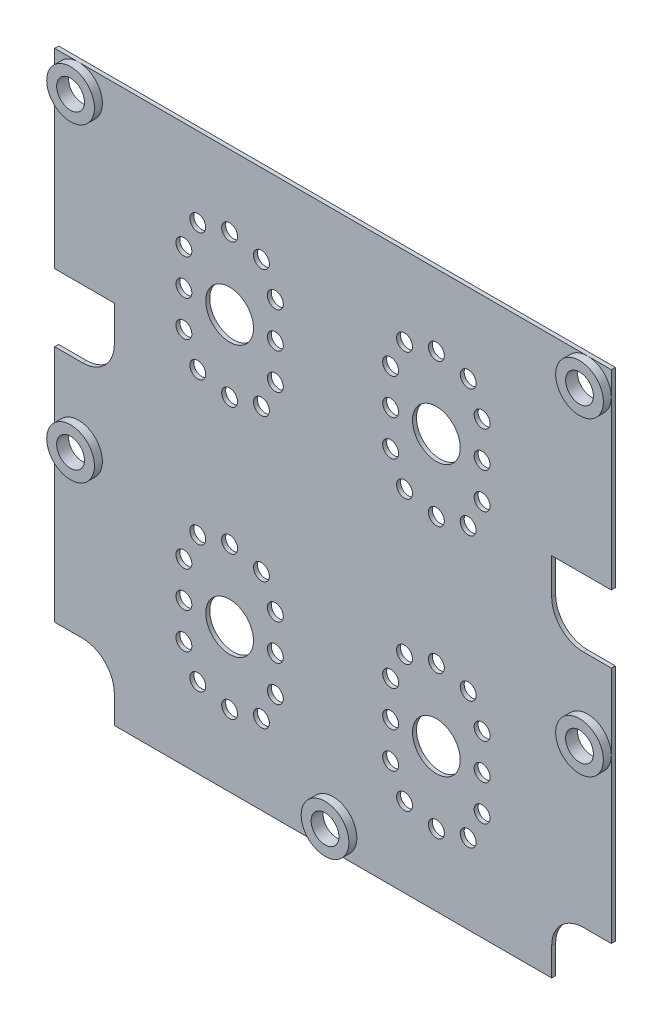
SolidWorks part; units mm, degrees
ref_plane "Front Plane" through (0, 0, 0) normal (0, 0, 1) x (1, 0, 0)
ref_plane "Top Plane" through (0, 0, 0) normal (0, 1, 0) x (1, 0, 0)
ref_plane "Right Plane" through (0, 0, 0) normal (1, 0, 0) x (0, 0, -1)
sketch "Sketch1" plane through (0, 0, 0) normal (0, 0, 1) x (1, 0, 0)
  line L1 (-35, -35) -> (35, -35)
  line L2 (-35, -35) -> (-35, 35)
  line L3 (-35, 35) -> (35, 35)
  line L4 (35, -35) -> (35, 35)
  line L5 (-35, -35) -> (35, 35) construction
  line L6 (-35, 35) -> (35, -35) construction
  point P0 (0, 0)
  dimension "D1" = 70
  dimension "D2" = 70
extrude "Boss-Extrude1" add sketch "Sketch1" along normal blind 0.5
sketch "Sketch2" plane through (0, 0, 0.5) normal (0, 0, 1) x (1, 0, 0)
  circle A0 centre (-13, 17) radius 3
  point P0 (-13, 17)
  dimension "D3" = 17
  dimension "D1" = 6
  dimension "D4" = 13
extrude "Cut-Extrude1" cut sketch "Sketch2" against normal through all
sketch "Sketch3" plane through (0, 0, 0.5) normal (0, 0, 1) x (1, 0, 0)
  line L0 (-13, 8) -> (-13, 26) construction
  line L1 (-7.25, 21.5) -> (-7.25, 12.5) construction
  line L2 (-9, 25) -> (-9, 9) construction
  line L3 (-13, 17) -> (-7.25, 17) construction
  circle A0 centre (-7.25, 21.5) radius 1
  circle A1 centre (-7.25, 17) radius 1
  circle A2 centre (-7.25, 12.5) radius 1
  circle A3 centre (-9, 9) radius 1
  circle A4 centre (-9, 25) radius 1
  circle A5 centre (-13, 26) radius 1
  circle A6 centre (-13, 8) radius 1
  circle A7 centre (-17, 9) radius 1
  circle A8 centre (-13, 17) radius 3 construction
  circle A9 centre (-18.75, 12.5) radius 1
  circle A10 centre (-18.75, 17) radius 1
  circle A11 centre (-18.75, 21.5) radius 1
  circle A12 centre (-17, 25) radius 1
  point P14 (-13, 17)
  point P18 (-9, 17)
  dimension "D4" = 2
  dimension "D1" = 18
  dimension "D2" = 8
  dimension "D3" = 11.5
  dimension "D5" = 16
  dimension "D6" = 9
extrude "Cut-Extrude2" cut sketch "Sketch3" against normal through all
mirror "Mirror1" about plane through (0, 0, 0) normal (1, 0, 0) of "Cut-Extrude2", "Cut-Extrude1"
mirror "Mirror2" about plane through (0, 0, 0) normal (0, 1, 0) of "Mirror1", "Cut-Extrude1", "Cut-Extrude2"
sketch "Sketch4" plane through (0, 0, 0.5) normal (0, 0, 1) x (1, 0, 0)
  line L1 (35, 35) -> (-35, 35) construction
  circle A0 centre (-32, 32) radius 3
  circle A1 centre (-32, -7) radius 3
  dimension "D4" = 6
  dimension "D1" = 32
  dimension "D2" = 39
  dimension "D3" = 3
extrude "Boss-Extrude2" add sketch "Sketch4" along normal blind 1
sketch "Sketch5" plane through (0, 0, 1.5) normal (0, 0, 1) x (1, 0, 0)
  circle A0 centre (-32, 32) radius 1.75
  circle A1 centre (-32, -7) radius 1.75
  dimension "D1" = 3.5
  dimension "D2" = 3.5
extrude "Cut-Extrude3" cut sketch "Sketch5" against normal through all
sketch "Sketch6" plane through (0, 0, 0.5) normal (0, 0, 1) x (1, 0, 0)
  line L1 (-36, -36) -> (-27.5, -36)
  line L2 (-36, -36) -> (-36, -27.5)
  line L3 (-36, -27.5) -> (-27.5, -27.5)
  line L4 (-27.5, -36) -> (-27.5, -27.5)
  line L5 (-36, 11) -> (-27.5, 11)
  line L6 (-36, 11) -> (-36, 2.5)
  line L7 (-36, 2.5) -> (-27.5, 2.5)
  line L8 (-27.5, 11) -> (-27.5, 2.5)
  line L9 (-36, 6.75) -> (-36, -31.75) construction
  point P13 (-2.3052, -0.8331)
  dimension "D1" = 8.5
  dimension "D2" = 38.5
  dimension "D3" = 36
  dimension "D4" = 36
extrude "Cut-Extrude4" cut sketch "Sketch6" against normal through all
fillet "Fillet1" radius 4 2 edges at (-27.5, -27.5, 0.25) (-27.5, 2.5, 0.25)
sketch "Sketch7" plane through (0, 0, 0.5) normal (0, 0, 1) x (1, 0, 0)
  line L0 (-27.5, -35) -> (35, -35) construction
  circle A0 centre (0, -32) radius 3
  dimension "D2" = 6
  dimension "D1" = 3
extrude "Boss-Extrude3" add sketch "Sketch7" along normal up to surface (1 mm away) up to face at (-30.25, 32, 1.5)
sketch "Sketch8" plane through (0, 0, 1.5) normal (0, 0, 1) x (1, 0, 0)
  circle A0 centre (0, -32) radius 1.75
  dimension "D1" = 3.5
extrude "Cut-Extrude5" cut sketch "Sketch8" against normal through all
mirror "Mirror3" about plane through (0, 0, 0) normal (1, 0, 0) of "Fillet1", "Cut-Extrude4", "Cut-Extrude3", "Boss-Extrude2"
